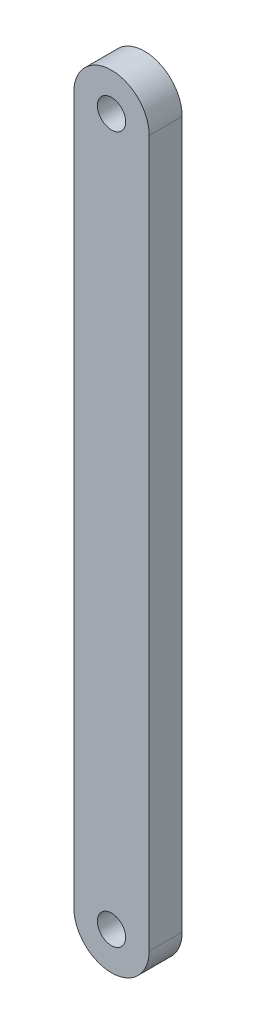
SolidWorks part; units mm, degrees
material "Balsa"
ref_plane "Front Plane" through (0, 0, 0) normal (0, 0, 1) x (1, 0, 0)
ref_plane "Top Plane" through (0, 0, 0) normal (0, 1, 0) x (1, 0, 0)
ref_plane "Right Plane" through (0, 0, 0) normal (1, 0, 0) x (0, 0, -1)
sketch "Sketch1" plane through (0, 0, 0) normal (0, 0, 1) x (1, 0, 0)
  line L0 (0, 0) -> (0, 75) construction
  line L1 (-4, 75) -> (-4, 0)
  line L2 (4, 0) -> (4, 75)
  arc A0 (-4, 75) -> (4, 75) centre (0, 75) cw
  arc A1 (-4, 0) -> (4, 0) centre (0, 0) ccw
  circle A2 centre (0, 75) radius 1.5
  circle A3 centre (0, 0) radius 1.5
  dimension "D2" = 4
  dimension "D3" = 3
  dimension "D1" = 75
extrude "Boss-Extrude1" add sketch "Sketch1" along normal blind 3.5
